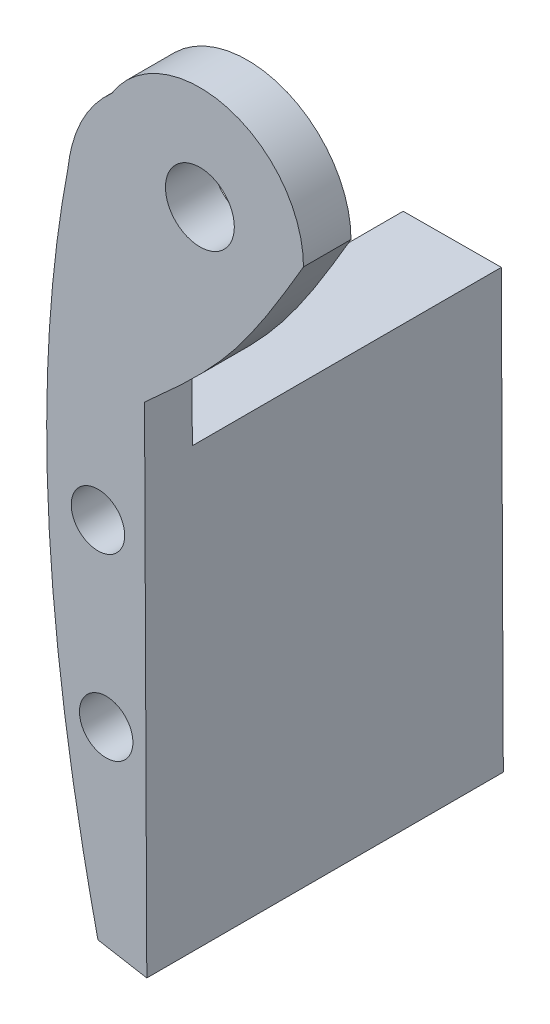
SolidWorks part; units mm, degrees
ref_plane "Front Plane" through (0, 0, 0) normal (0, 0, 1) x (1, 0, 0)
ref_plane "Top Plane" through (0, 0, 0) normal (0, 1, 0) x (1, 0, 0)
ref_plane "Right Plane" through (0, 0, 0) normal (1, 0, 0) x (0, 0, -1)
sketch "Sketch1" plane through (0, 0, 0) normal (0, 0, 1) x (1, 0, 0)
  line L49 (-14.1534, -69.7169) -> (-10.0398, -70.4384)
  line L50 (-10.0398, -70.4384) -> (-10.2316, -28.5481)
  arc A48 (3.1505, -12) -> (-12.9862, -7.4065) centre (-5.5716, -12) ccw
  circle A49 centre (-5.5716, -12) radius 2.9
  spline S2 degree 3 poles (-18.4013, -30.5146) (-18.849, -43.6728) (-17.0302, -56.9394) (-14.1534, -69.7169) knots 0.288119 0.288119 0.288119 0.288119 1 1 1 1
  spline S3 degree 3 poles (-16.6639, -14.6308) (-17.6677, -19.8813) (-18.2201, -25.189) (-18.4013, -30.5146) knots 0 0 0 0 0.288119 0.288119 0.288119 0.288119
  spline S4 degree 2 poles (-16.6639, -14.6308) (-16.1578, -10.2368) (-12.9862, -7.4065) knots 0 0 0 1 1 1
  spline S5 degree 3 poles (3.1505, -12) (1.1214, -15.4485) (-2.5224, -21.6413) (-7.8644, -26.4273) (-10.2316, -28.5481) knots 0 0 0 0 0.556866 1 1 1 1
  dimension "D1" = 5.8
extrude "Boss-Extrude1" add sketch "Sketch1" against normal blind 4
sketch "Sketch2" plane through (0, 0, -4) normal (0, 0, -1) x (-1, 0, 0)
  line L1 (10.2079, -33.7171) -> (18.4664, -33.7549)
  line L6 (10.2316, -28.5481) -> (10.0398, -70.4384)
  line L7 (10.0398, -70.4384) -> (14.1534, -69.7169)
  line L8 (10.2079, -33.7171) -> (10.0398, -70.4384)
  line L9 (10.0398, -70.4384) -> (14.1534, -69.7169)
  arc A1 (12.9862, -7.4065) -> (-3.1505, -12) centre (5.5716, -12) ccw
  circle A5 centre (14.1522, -39.1038) radius 2.25
  parabola Q1 (16.6639, -14.6308) -> (12.9862, -7.4065) focus (10.6183, -12.7527) apex (15.1874, -10.0721)
  spline S3 degree 3 poles (938.4764, 361.2251) (-1091.2534, -828.2679) (1122.0204, 453.267) (-983.2612, -26.7933) knots -8.11143 -8.11143 -8.11143 -8.11143 5.561586 5.561586 5.561586 5.561586 only from (18.4013, -30.5146) to (16.6639, -14.6308)
  spline S4 degree 3 poles (-852.3579, -540.0542) (21.0399, 119.8389) (-73.3283, -80.1542) (129.3516, -34.0846) (-674.0117, -757.7862) knots -6.347213 -6.347213 -6.347213 -6.347213 0.556866 6.878353 6.878353 6.878353 6.878353 only from (-3.1505, -12) to (10.2316, -28.5481)
  spline S5 degree 3 poles (3516.6249, 1855.3727) (-3838.1047, -2361.8613) (3969.2228, 1793.0927) (-3850.0353, -900.9084) knots -10.651246 -10.651246 -10.651246 -10.651246 10.296801 10.296801 10.296801 10.296801 only from (14.1534, -69.7169) to (18.4013, -30.5146)
  spline S8 degree 3 poles (14.1534, -69.7169) (16.7942, -57.9876) (18.5434, -45.8463) (18.4664, -33.7549) knots 0.288119 0.288119 0.288119 0.288119 0.941598 0.941598 0.941598 0.941598
  dimension "D1" = 0
extrude "Boss-Extrude2" add sketch "Sketch2" along normal blind 26.0124
sketch "Sketch3" plane through (0, 0, 0) normal (0, 0, 1) x (1, 0, 0)
  circle A1 centre (-13.4597, -53.8503) radius 2.25
  circle A3 centre (-14.1522, -39.1038) radius 2.25
  point P4 (0, 0)
  point P6 (0, 0)
  dimension "D2" = 4.5
extrude "Cut-Extrude1" cut sketch "Sketch3" against normal through all
